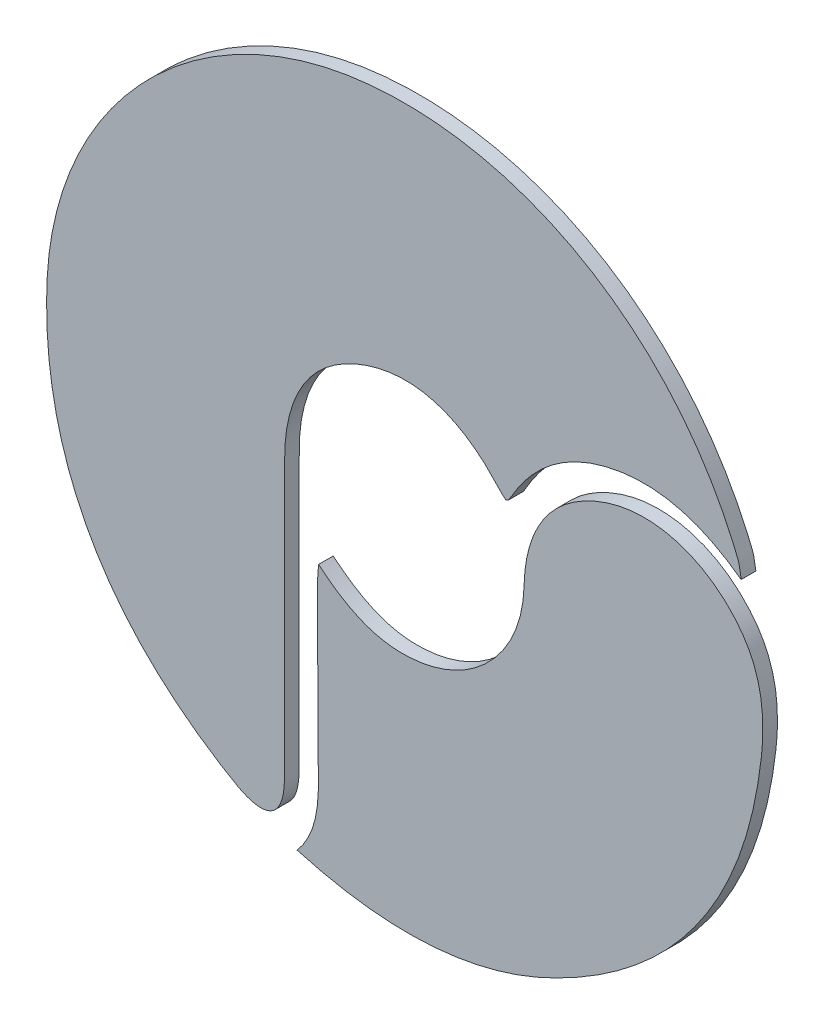
SolidWorks part; units mm, degrees
ref_plane "Front Plane" through (0, 0, 0) normal (0, 0, 1) x (1, 0, 0)
ref_plane "Top Plane" through (0, 0, 0) normal (0, 1, 0) x (1, 0, 0)
ref_plane "Right Plane" through (0, 0, 0) normal (1, 0, 0) x (0, 0, -1)
sketch "Model" plane through (0, 0, 0) normal (0, 0, 1) x (1, 0, 0)
  line L0 (25.3017, -9.9366) -> (25.2979, -9.9409)
  spline S0 degree 3 poles (10.8886, -16.6988) (10.8735, -16.9151) (10.8564, -17.044) (10.8567, -17.1728) (10.8616, -19.0756) (10.8483, -20.9788) (10.884, -22.881) (10.9016, -23.8138) (10.8334, -24.7014) (10.1593, -25.5016) knots 7 7 7 7 8 8 8 9 9 9 10 10 10 10
  spline S1 degree 3 poles (10.1593, -25.5016) (13.132, -26.351) (16.0125, -26.2782) (18.7311, -24.9866) (22.9556, -22.9796) (25.4392, -19.6119) (25.9782, -14.9155) (26.1247, -13.6397) (26.0504, -12.368) (25.1799, -11.3029) (24.0527, -9.9238) (22.271, -9.418) (20.6365, -9.9937) (18.8918, -10.6082) (17.9415, -11.9365) (17.8973, -13.8224) (17.8438, -16.1113) (16.0001, -17.9129) (13.7263, -17.9001) (12.6481, -17.8941) (11.7549, -17.4243) (10.8886, -16.6988) knots 0 0 0 0 1 1 1 2 2 2 3 3 3 4 4 4 5 5 5 6 6 6 7 7 7 7
  spline S2 degree 3 poles (17.2789, -11.603) (17.3395, -11.5703) (17.363, -11.5655) (17.3723, -11.5513) (17.4156, -11.4856) (17.4558, -11.4179) (17.4956, -11.3499) (18.3027, -9.9708) (19.4788, -9.1148) (21.0611, -8.835) (22.6424, -8.5554) (24.0339, -9.0042) (25.2979, -9.9409) knots 11 11 11 11 12 12 12 13 13 13 14 14 14 15 15 15 15
  spline S3 degree 3 poles (25.3017, -9.9366) (25.2626, -9.7475) (25.2514, -9.5471) (25.1803, -9.3709) (22.984, -3.922) (17.7372, -1.0343) (12.2755, -1.7012) (6.5941, -2.3949) (1.8904, -7.2624) (1.6327, -12.93) (1.3993, -18.0641) (3.5678, -21.9674) (8.0196, -24.5662) (9.1067, -25.2008) (9.7257, -24.8268) (9.7262, -23.5787) (9.7276, -20.444) (9.7218, -17.3093) (9.7286, -14.1746) (9.733, -12.1287) (10.6519, -10.7059) (12.3608, -10.0622) (14.0981, -9.4078) (15.7439, -9.8866) (17.0911, -11.4358) (17.1495, -11.503) (17.2248, -11.5554) (17.2789, -11.603) knots 2 2 2 2 3 3 3 4 4 4 5 5 5 6 6 6 7 7 7 8 8 8 9 9 9 10 10 10 11 11 11 11
  spline S4 degree 3 poles (25.3876, -9.9732) (25.3589, -9.961) (25.3303, -9.9488) (25.3017, -9.9366) knots 1 1 1 1 2 2 2 2
  spline S5 degree 3 poles (25.2979, -9.9409) (25.3278, -9.9517) (25.3577, -9.9624) (25.3876, -9.9732) knots 0 0 0 0 1 1 1 1
  spline S6 degree 3 poles (27.1998, -0.3002) (27.1998, -9.2705) (27.1998, -18.237) (27.1998, -27.1998) knots 3 3 3 3 4 4 4 4
  spline S7 degree 3 poles (0.3002, -0.3002) (9.2705, -0.3002) (18.237, -0.3002) (27.1998, -0.3002) knots 2 2 2 2 3 3 3 3
  spline S8 degree 3 poles (0.3002, -27.1998) (0.3002, -18.2295) (0.3002, -9.263) (0.3002, -0.3002) knots 1 1 1 1 2 2 2 2
  spline S9 degree 3 poles (27.1998, -27.1998) (18.2295, -27.1998) (9.263, -27.1998) (0.3002, -27.1998) knots 0 0 0 0 1 1 1 1
  spline S10 degree 3 poles (25.2979, -9.9409) (24.0339, -9.0042) (22.6424, -8.5554) (21.0611, -8.835) knots 0 0 0 0 1 1 1 1
  spline S11 degree 3 poles (21.0611, -8.835) (19.4788, -9.1148) (18.3027, -9.9708) (17.4956, -11.3499) knots 1 1 1 1 2 2 2 2
  spline S12 degree 3 poles (17.4956, -11.3499) (17.4558, -11.4179) (17.4156, -11.4856) (17.3723, -11.5513) knots 2 2 2 2 3 3 3 3
  spline S13 degree 3 poles (17.3723, -11.5513) (17.363, -11.5655) (17.3395, -11.5703) (17.2789, -11.603) knots 3 3 3 3 4 4 4 4
  spline S14 degree 3 poles (17.2789, -11.603) (17.2248, -11.5554) (17.1495, -11.503) (17.0911, -11.4358) knots 4 4 4 4 5 5 5 5
  spline S15 degree 3 poles (17.0911, -11.4358) (15.7439, -9.8866) (14.0981, -9.4078) (12.3608, -10.0622) knots 5 5 5 5 6 6 6 6
  spline S16 degree 3 poles (12.3608, -10.0622) (10.6519, -10.7059) (9.733, -12.1287) (9.7286, -14.1746) knots 6 6 6 6 7 7 7 7
  spline S17 degree 3 poles (9.7286, -14.1746) (9.7218, -17.3093) (9.7276, -20.444) (9.7262, -23.5787) knots 7 7 7 7 8 8 8 8
  spline S18 degree 3 poles (9.7262, -23.5787) (9.7257, -24.8268) (9.1067, -25.2008) (8.0196, -24.5662) knots 8 8 8 8 9 9 9 9
  spline S19 degree 3 poles (8.0196, -24.5662) (3.5678, -21.9674) (1.3993, -18.0641) (1.6327, -12.93) knots 9 9 9 9 10 10 10 10
  spline S20 degree 3 poles (1.6327, -12.93) (1.8904, -7.2624) (6.5941, -2.3949) (12.2755, -1.7012) knots 10 10 10 10 11 11 11 11
  spline S21 degree 3 poles (12.2755, -1.7012) (17.7372, -1.0343) (22.984, -3.922) (25.1803, -9.3709) knots 11 11 11 11 12 12 12 12
  spline S22 degree 3 poles (25.1803, -9.3709) (25.2514, -9.5471) (25.2626, -9.7475) (25.3017, -9.9366) knots 12 12 12 12 13 13 13 13
  spline S23 degree 3 poles (10.8886, -16.6988) (11.7549, -17.4243) (12.6481, -17.8941) (13.7263, -17.9001) (16.0001, -17.9129) (17.8438, -16.1113) (17.8973, -13.8224) (17.9415, -11.9365) (18.8918, -10.6082) (20.6365, -9.9937) (22.271, -9.418) (24.0527, -9.9238) (25.1799, -11.3029) (26.0504, -12.368) (26.1247, -13.6397) (25.9782, -14.9155) (25.4392, -19.6119) (22.9556, -22.9796) (18.7311, -24.9866) (16.0125, -26.2782) (13.132, -26.351) (10.1593, -25.5016) knots 3 3 3 3 4 4 4 5 5 5 6 6 6 7 7 7 8 8 8 9 9 9 10 10 10 10
  spline S24 degree 3 poles (10.1593, -25.5016) (10.8334, -24.7014) (10.9016, -23.8138) (10.884, -22.881) (10.8483, -20.9788) (10.8616, -19.0756) (10.8567, -17.1728) (10.8564, -17.044) (10.8735, -16.9151) (10.8886, -16.6988) knots 0 0 0 0 1 1 1 2 2 2 3 3 3 3
  spline S25 degree 3 poles (25.3017, -9.9366) (25.3303, -9.9488) (25.3589, -9.961) (25.3876, -9.9732) knots 0 0 0 0 1 1 1 1
  spline S26 degree 3 poles (25.3876, -9.9732) (25.3577, -9.9624) (25.3278, -9.9517) (25.2979, -9.9409) knots 1 1 1 1 2 2 2 2
extrude "Boss-Extrude1" add sketch "Model" along normal blind 0.5 contours L0 S3 S2 | S0 S1
